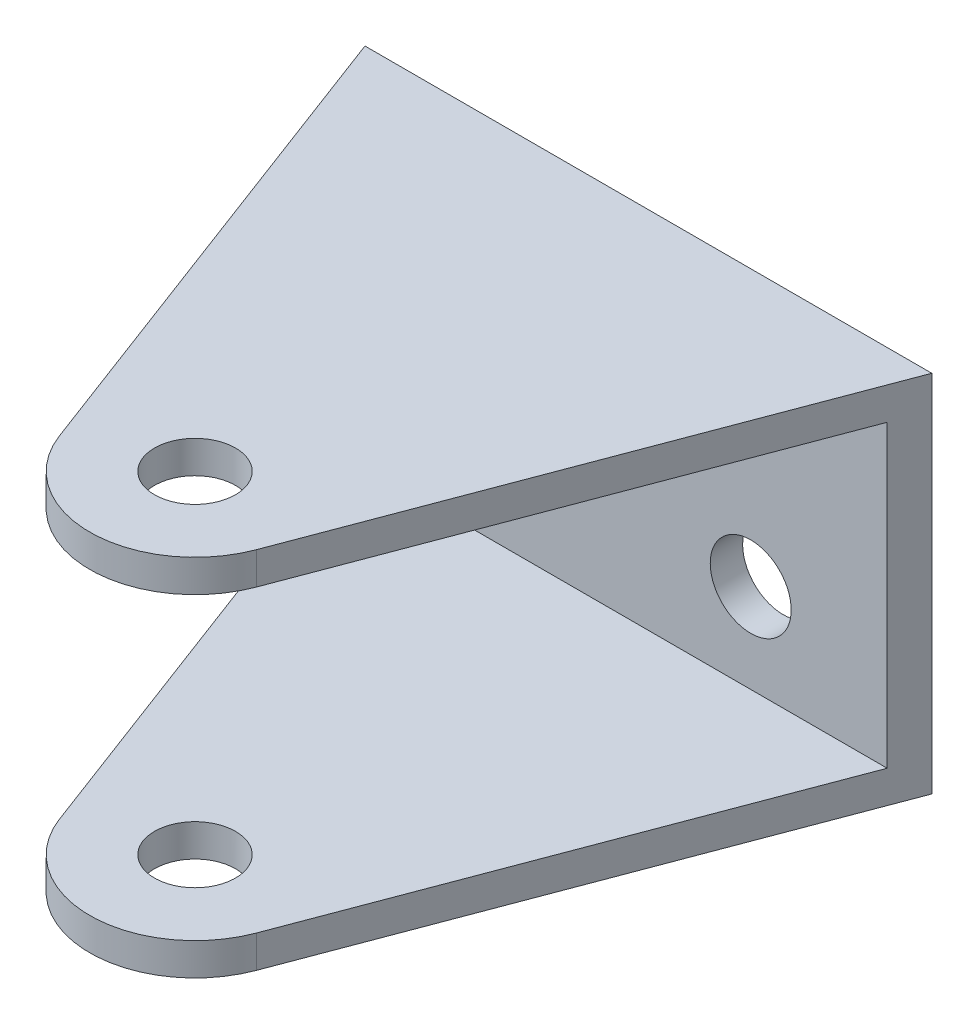
SolidWorks part; units mm, degrees
ref_plane "Front Plane" through (0, 0, 0) normal (0, 0, 1) x (1, 0, 0)
ref_plane "Top Plane" through (0, 0, 0) normal (0, 1, 0) x (1, 0, 0)
ref_plane "Right Plane" through (0, 0, 0) normal (1, 0, 0) x (0, 0, -1)
sketch "Sketch1" plane through (0, 0, 32.9) normal (0, 0, 1) x (1, 0, 0)
  line L0 (-17.5, 114.3) -> (17.5, 114.3) construction
  line L1 (37.241, 99.2999) -> (-37.241, 99.2999) construction
  line L2 (-34.1417, 99.2999) -> (35.8583, 99.2999)
  line L3 (-34.1417, 99.2999) -> (-34.1417, 144.2999)
  line L5 (35.8583, 99.2999) -> (35.8583, 144.2999)
  line L6 (-34.1417, 144.2999) -> (35.8583, 144.2999)
  circle A0 centre (-17.5, 114.3) radius 5 construction
  circle A1 centre (-17.5, 114.3) radius 5
  circle A2 centre (17.5, 114.3) radius 5 construction
  circle A3 centre (17.5, 114.3) radius 5
  point P0 (0, 114.3)
  dimension "D1" = 45
  dimension "D2" = 70
extrude "Boss-Extrude1" add sketch "Sketch1" along normal blind 70
sketch "Sketch2" plane through (0, 144.2999, 0) normal (0, 1, 0) x (1, 0, 0)
  line L0 (0.8583, -102.9) -> (0.8583, -32.9) construction
  line L1 (35.8583, -102.9) -> (-34.1417, -102.9) construction
  line L2 (35.8583, -32.9) -> (-34.1417, -32.9) construction
  line L3 (35.8583, -32.9) -> (13.0226, -93.4757)
  line L4 (-34.1417, -32.9) -> (-11.3061, -93.4757)
  line L5 (35.8583, -32.9) -> (51.1912, -32.9)
  line L6 (51.1912, -32.9) -> (51.1912, -140.3006)
  line L7 (51.1912, -140.3006) -> (-47.1946, -140.3006)
  line L8 (-47.1946, -140.3006) -> (-47.1946, -32.9)
  line L9 (-47.1946, -32.9) -> (-34.1417, -32.9)
  circle A0 centre (0.8583, -88.89) radius 5
  circle A1 centre (0.8583, -88.89) radius 13
  line M6 (-34.1417, -32.9) -> (-34.1417, -102.9)
  line M7 (-34.1417, -102.9) -> (35.8583, -102.9)
  line M8 (35.8583, -102.9) -> (35.8583, -32.9)
  dimension "D1" = 8
  dimension "D3" = 10
  dimension "D2" = 55.99
extrude "Cut-Extrude1" cut sketch "Sketch2" against normal blind 70 contours L0 L3 A1 M7 M8 | L0 A1 L4 M7 M6 | A0
sketch "Sketch3" plane through (0, 0, 0) normal (1, 0, 0) x (0, 0, -1)
  line L0 (-32.9, 144.2999) -> (-32.9, 99.2999) construction
  line L1 (-32.9, 144.2999) -> (-32.9, 99.2999)
  line L2 (-32.9, 121.7999) -> (-105.7938, 121.7999) construction
  line L3 (-36.9, 140.2999) -> (-109.1356, 140.2999)
  line L4 (-109.1356, 140.2999) -> (-109.1356, 103.2999)
  line L5 (-109.1356, 103.2999) -> (-36.9, 103.2999)
  line L6 (-36.9, 103.2999) -> (-36.9, 140.2999)
  line L7 (-32.9, 144.2999) -> (-93.4757, 144.2999) construction
  line L8 (-32.9, 99.2999) -> (-93.4757, 99.2999) construction
  dimension "D1" = 4
  dimension "D2" = 4
  dimension "D3" = 4
extrude "Cut-Extrude2" cut sketch "Sketch3" against normal through all both and the other way through all
equation "\"D2@Sketch3\"=\"D1@Sketch3\""
equation "\"D3@Sketch3\"=\"D1@Sketch3\""
